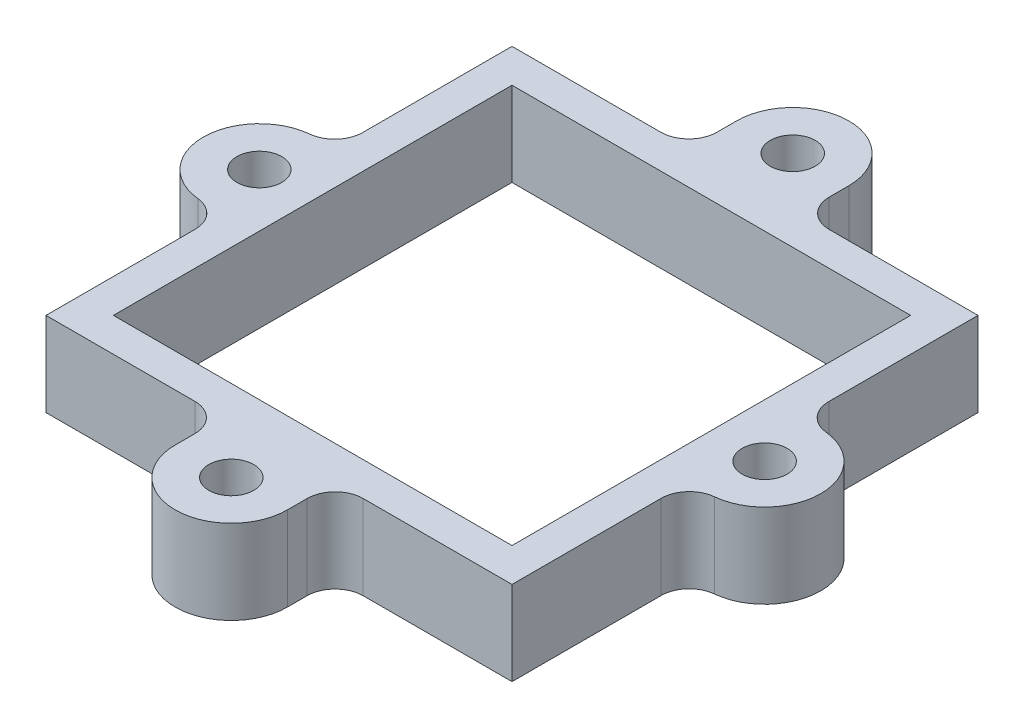
SolidWorks part; units mm, degrees
ref_plane "Front Plane" through (0, 0, 0) normal (0, 0, 1) x (1, 0, 0)
ref_plane "Top Plane" through (0, 0, 0) normal (0, 1, 0) x (1, 0, 0)
ref_plane "Right Plane" through (0, 0, 0) normal (1, 0, 0) x (0, 0, -1)
sketch "Sketch1" plane through (0, 0, 0) normal (0, 1, 0) x (1, 0, 0)
  line L0 (9, 0) -> (-9, 0) construction
  line L1 (-7.1, 7.1) -> (7.1, 7.1)
  line L2 (-7.1, 7.1) -> (-7.1, -7.1)
  line L3 (-7.1, -7.1) -> (7.1, -7.1)
  line L4 (7.1, 7.1) -> (7.1, -7.1)
  line L5 (-7.1, 7.1) -> (7.1, -7.1) construction
  line L6 (-7.1, -7.1) -> (7.1, 7.1) construction
  line L7 (0, 10) -> (0, -10) construction
  line L8 (-9, 0) -> (9, 0) construction
  line L9 (-9, 2) -> (-8.3, 2)
  line L10 (-9, -2) -> (-8.3, -2)
  line L11 (0, -10) -> (0, 10) construction
  line L12 (-2, -10) -> (-2, -8.3)
  line L13 (2, -10) -> (2, -8.3)
  line L14 (-8.3, 8.3) -> (-8.3, 2)
  line L15 (-8.3, -8.3) -> (-2, -8.3)
  line L16 (8.3, 8.3) -> (8.3, 2)
  line L17 (-8.3, 8.3) -> (-2, 8.3)
  line L18 (8.3, 2) -> (9, 2)
  line L19 (2, -8.3) -> (8.3, -8.3)
  line L20 (-2, 8.3) -> (-2, 10)
  line L21 (-8.3, 8.3) -> (-8.3, -8.3) construction
  line L22 (-8.3, -2) -> (-8.3, -8.3)
  line L23 (2, 8.3) -> (2, 10)
  line L24 (8.3, -2) -> (9, -2)
  line L25 (-8.3, -8.3) -> (8.3, -8.3) construction
  line L26 (2, 8.3) -> (8.3, 8.3)
  line L27 (8.3, 8.3) -> (8.3, -8.3) construction
  line L28 (8.3, -2) -> (8.3, -8.3)
  line L29 (-8.3, 8.3) -> (8.3, 8.3) construction
  circle A0 centre (0, 10) radius 0.8 construction
  circle A1 centre (-9, 0) radius 0.8 construction
  circle A2 centre (0, -10) radius 0.8 construction
  circle A3 centre (9, 0) radius 0.8 construction
  arc A4 (-9, 2) -> (-9, -2) centre (-9, 0) ccw
  arc A5 (9, -2) -> (9, 2) centre (9, 0) ccw
  arc A6 (-2, -10) -> (2, -10) centre (0, -10) ccw
  arc A7 (2, 10) -> (-2, 10) centre (0, 10) ccw
  point P0 (0, 0)
  point P9 (0, 0)
  point P12 (0, 0)
  point P16 (0, 0)
  point P21 (0, 0)
  dimension "D4" = 1.6
  dimension "D6" = 1.2
  dimension "D7" = 1.2
  dimension "D1" = 14.2
  dimension "D2" = 18
  dimension "D3" = 20
  dimension "D5" = 1.2
extrude "Boss-Extrude1" add sketch "Sketch1" along normal blind 3
sketch "Sketch2" plane through (0, 3, 0) normal (0, 1, 0) x (1, 0, 0)
  circle A0 centre (0, 10) radius 0.8 construction
  circle A1 centre (9, 0) radius 0.8 construction
  circle A2 centre (0, -10) radius 0.8 construction
  circle A3 centre (-9, 0) radius 0.8 construction
  circle A4 centre (0, 10) radius 0.8
  circle A5 centre (9, 0) radius 0.8
  circle A6 centre (0, -10) radius 0.8
  circle A7 centre (-9, 0) radius 0.8
extrude "Cut-Extrude1" cut sketch "Sketch2" against normal through all
fillet "Fillet1" radius 1 8 edges at (-2, 1.5, 8.3) (2, 1.5, 8.3) (8.3, 1.5, 2) (8.3, 1.5, -2) (2, 1.5, -8.3) (-2, 1.5, -8.3) (-8.3, 1.5, -2) (-8.3, 1.5, 2)
